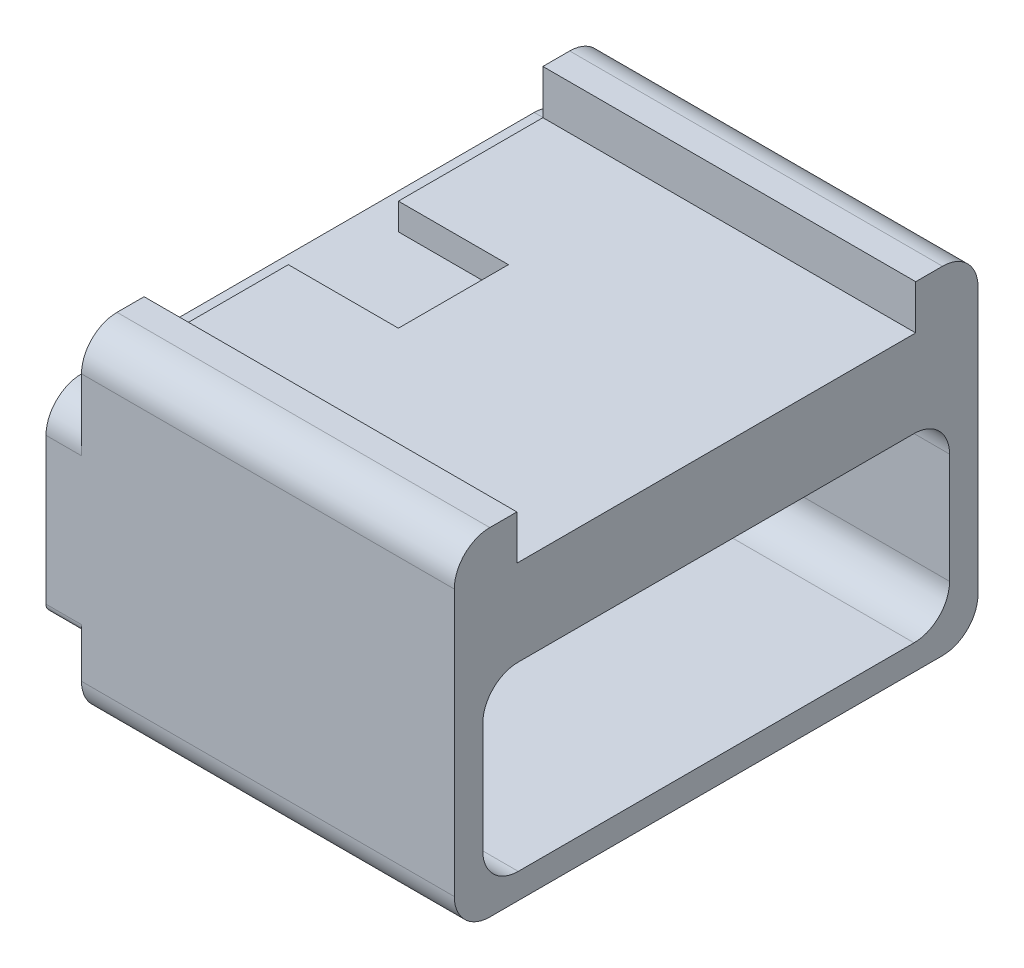
SolidWorks part; units mm, degrees
ref_plane "Front Plane" through (0, 0, 0) normal (0, 0, 1) x (1, 0, 0)
ref_plane "Top Plane" through (0, 0, 0) normal (0, 1, 0) x (1, 0, 0)
ref_plane "Right Plane" through (0, 0, 0) normal (1, 0, 0) x (0, 0, -1)
sketch "Sketch3" plane through (0, 0, 0) normal (1, 0, 0) x (0, 0, -1)
  line L0 (-12.75, -9.5) -> (12.75, -9.5)
  line L1 (-14.75, -7.5) -> (-14.75, 7.5)
  line L2 (-12.75, 9.5) -> (12.75, 9.5)
  line L3 (14.75, -7.5) -> (14.75, 7.5)
  line L4 (0, 9.5) -> (0, -9.5) construction
  line L5 (14.75, 0) -> (-14.75, 0) construction
  arc A0 (14.75, -7.5) -> (12.75, -9.5) centre (12.75, -7.5) cw
  arc A1 (-14.75, -7.5) -> (-12.75, -9.5) centre (-12.75, -7.5) ccw
  arc A2 (-12.75, 9.5) -> (-14.75, 7.5) centre (-12.75, 7.5) ccw
  arc A3 (12.75, 9.5) -> (14.75, 7.5) centre (12.75, 7.5) cw
  point P16 (0, 0)
  dimension "D3" = 2
  dimension "D1" = 19
  dimension "D2" = 25.5
extrude "Boss-Extrude1" add sketch "Sketch3" along normal blind 21
sketch "Sketch5" plane through (0, 9.5, 0) normal (0, 1, 0) x (1, 0, 0)
  line L0 (0, 12.75) -> (0, -12.75) construction
  line L1 (6.2, 3.1) -> (0, 3.1)
  line L2 (6.2, 3.1) -> (6.2, -3.1)
  line L3 (6.2, -3.1) -> (0, -3.1)
  line L4 (0, 3.1) -> (0, -3.1)
  line L5 (6.2, 0) -> (0, 0) construction
  dimension "D1" = 6.2
  dimension "D2" = 6.2
extrude "Cut-Extrude1" cut sketch "Sketch5" against normal blind 4
sketch "Sketch7" plane through (0, 0, 0) normal (-1, 0, 0) x (0, 0, 1)
  line L0 (0, 2.1353) -> (0, -8.0729) construction
  line L1 (-11.1476, -8.0729) -> (11.1476, -8.0729)
  line L2 (-13.1476, -6.0729) -> (-13.1476, 0.1353)
  line L3 (-11.1476, 2.1353) -> (11.1476, 2.1353)
  line L4 (13.1476, -6.0729) -> (13.1476, 0.1353)
  line L5 (12.75, -9.5) -> (-12.75, -9.5) construction
  arc A0 (11.1476, -8.0729) -> (13.1476, -6.0729) centre (11.1476, -6.0729) ccw
  arc A1 (11.1476, 2.1353) -> (13.1476, 0.1353) centre (11.1476, 0.1353) cw
  arc A2 (-13.1476, 0.1353) -> (-11.1476, 2.1353) centre (-11.1476, 0.1353) cw
  arc A3 (-13.1476, -6.0729) -> (-11.1476, -8.0729) centre (-11.1476, -6.0729) ccw
  point P6 (0, -2.9688)
  point P7 (0, -9.5)
  dimension "D1" = 2
extrude "Cut-Extrude2" cut sketch "Sketch7" against normal through all both and the other way through all
sketch "Sketch9" plane through (0, 9.5, 0) normal (0, 1, 0) x (1, 0, 0)
  line L0 (0, 12.75) -> (0, 3.1) construction
  line L1 (0, 11.24) -> (24.2849, 11.24)
  line L2 (0, 11.24) -> (0, -11.2248)
  line L3 (0, -11.2248) -> (24.2849, -11.2248)
  line L4 (24.2849, 11.24) -> (24.2849, -11.2248)
  line L5 (24.2849, 0.0076) -> (0, 0.0076) construction
  line L6 (6.2, -3.1) -> (6.2, 3.1) construction
  point P8 (6.2, 0)
  point P12 (6.2, -0.2283)
extrude "Cut-Extrude3" cut sketch "Sketch9" against normal blind 2.5
sketch "Sketch10" plane through (21, 0, 0) normal (1, 0, 0) x (0, 0, -1)
  line L1 (-15.9191, 11.2845) -> (15.8968, 11.2845)
  line L2 (-15.9191, 11.2845) -> (-15.9191, -10.3889)
  line L3 (-15.9191, -10.3889) -> (15.8968, -10.3889)
  line L4 (15.8968, 11.2845) -> (15.8968, -10.3889)
sketch "Sketch11" plane through (0, 0, 0) normal (-1, 0, 0) x (0, 0, 1)
  line L0 (-13.6476, -5.2351) -> (-14.25, -5.2351)
  line L1 (-13.1476, 0.1353) -> (-13.1476, -6.0729) construction
  line L2 (-14.75, -7.5) -> (-14.75, 7.5) construction
  line L3 (-14.75, -4.7351) -> (-14.75, 3.5)
  line L4 (-12.75, 5.5) -> (12.75, 5.5)
  line L5 (14.75, 7.5) -> (14.75, -7.5) construction
  line L6 (14.75, 3.5) -> (14.75, -4.7351)
  line L7 (14.25, -5.2351) -> (13.6476, -5.2351)
  line L8 (13.1476, -6.0729) -> (13.1476, 0.1353) construction
  line L9 (-13.1476, -4.7351) -> (-13.1476, 0.1353)
  line L10 (-11.1476, 2.1353) -> (11.1476, 2.1353)
  line L11 (13.1476, 0.1353) -> (13.1476, -4.7351)
  line L12 (-3.1, 5.5) -> (3.1, 5.5) construction
  line L13 (11.1476, 2.1353) -> (-11.1476, 2.1353) construction
  arc A0 (11.1476, 2.1353) -> (13.1476, 0.1353) centre (11.1476, 0.1353) cw
  arc A1 (-13.1476, 0.1353) -> (-11.1476, 2.1353) centre (-11.1476, 0.1353) cw
  arc A2 (12.75, 5.5) -> (14.75, 3.5) centre (12.75, 3.5) cw
  arc A3 (-14.75, 3.5) -> (-12.75, 5.5) centre (-12.75, 3.5) cw
  arc A4 (13.6476, -5.2351) -> (13.1476, -4.7351) centre (13.6476, -4.7351) cw
  arc A5 (-13.6476, -5.2351) -> (-13.1476, -4.7351) centre (-13.6476, -4.7351) ccw
  arc A6 (14.75, -4.7351) -> (14.25, -5.2351) centre (14.25, -4.7351) cw
  arc A7 (-14.25, -5.2351) -> (-14.75, -4.7351) centre (-14.25, -4.7351) cw
  point P26 (14.75, 5.5)
  point P29 (-14.75, 5.5)
  point P32 (13.1476, -5.2351)
  point P35 (-13.1476, -5.2351)
  point P38 (14.75, -5.2351)
  point P41 (-14.75, -5.2351)
  dimension "D1" = 2
  dimension "D2" = 2
  dimension "D3" = 0.5
extrude "Boss-Extrude2" add sketch "Sketch11" along normal blind 2
